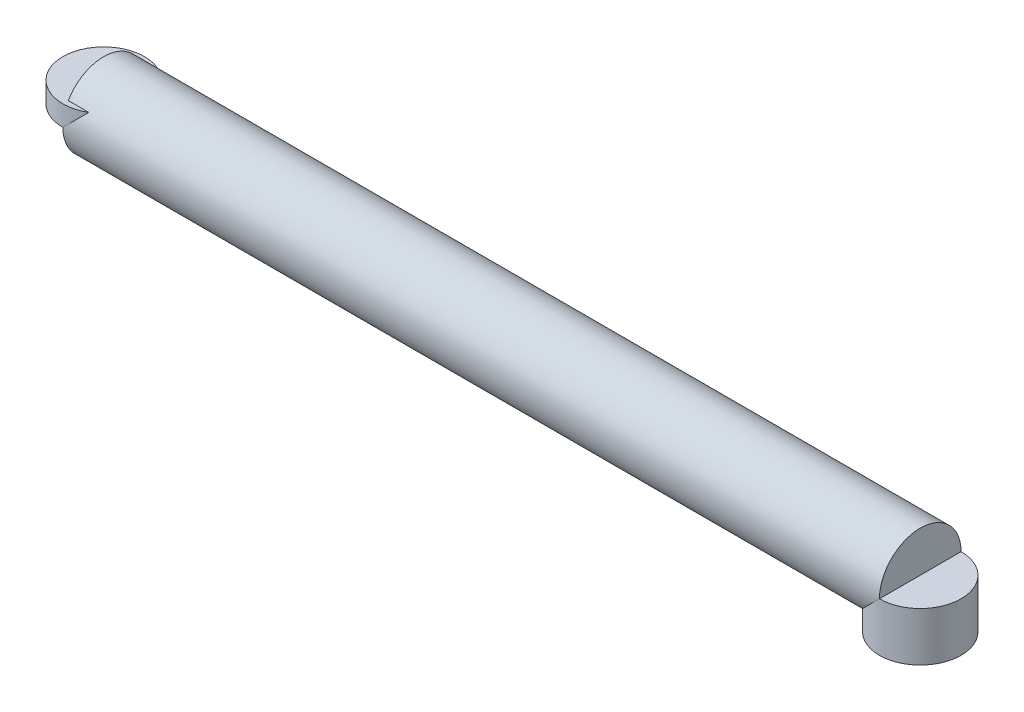
SolidWorks part; units mm, degrees
ref_plane "Front Plane" through (0, 0, 0) normal (0, 0, 1) x (1, 0, 0)
ref_plane "Top Plane" through (0, 0, 0) normal (0, 1, 0) x (1, 0, 0)
ref_plane "Right Plane" through (0, 0, 0) normal (1, 0, 0) x (0, 0, -1)
ref_plane "Plane1" through (0, 71.8, 0) normal (0, 1, 0) x (1, 0, 0)
sketch "Sketch1" plane through (0, 71.8, 0) normal (0, 1, 0) x (1, 0, 0)
  circle A0 centre (24, -16.7) radius 1
extrude "Boss-Extrude1" add sketch "Sketch1" along normal blind 1.2
ref_plane "Plane2" through (4, 0, 0) normal (1, 0, 0) x (0, 0, -1)
sketch "Sketch2" plane through (4, 0, 0) normal (1, 0, 0) x (0, 0, -1)
  circle A0 centre (-16.7, 73) radius 1
extrude "Boss-Extrude2" add sketch "Sketch2" along normal blind 20
ref_plane "Plane3" through (0, 73, 0) normal (0, 1, 0) x (1, 0, 0)
sketch "Sketch3" plane through (0, 73, 0) normal (0, 1, 0) x (1, 0, 0)
  circle A0 centre (4, -16.7) radius 1
extrude "Boss-Extrude3" add sketch "Sketch3" along normal blind 0.5
